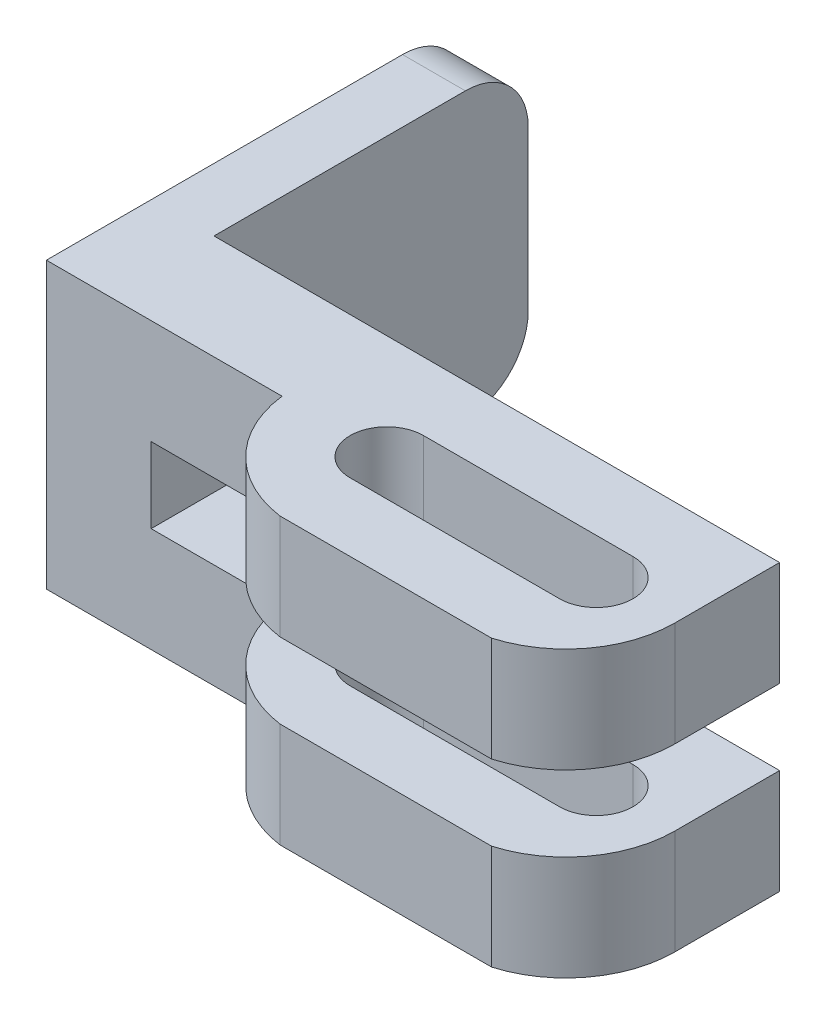
SolidWorks part; units mm, degrees
ref_plane "Alzado" through (0, 0, 0) normal (0, 0, 1) x (1, 0, 0)
ref_plane "Planta" through (0, 0, 0) normal (0, 1, 0) x (1, 0, 0)
ref_plane "Vista lateral" through (0, 0, 0) normal (1, 0, 0) x (0, 0, -1)
sketch "Croquis1" plane through (0, 0, 0) normal (0, 0, 1) x (1, 0, 0)
  line L0 (0, 0) -> (-90, 0) construction
  line L1 (-90, -6.8) -> (-90, -1.8)
  line L2 (-90, -1.8) -> (-65, -1.8)
  line L3 (-65, -1.8) -> (-65, 1.8)
  line L4 (-90, -6.8) -> (90, -6.8)
  line L5 (0, 0) -> (0, -28.0002) construction
  line L6 (-90, 6.8) -> (-90, 1.8)
  line L7 (-90, 1.8) -> (-65, 1.8)
  line L8 (-90, 6.8) -> (90, 6.8)
  line L9 (90, 6.8) -> (90, 1.8)
  line L10 (90, 1.8) -> (65, 1.8)
  line L11 (65, -1.8) -> (65, 1.8)
  line L12 (90, -6.8) -> (90, -1.8)
  line L13 (90, -1.8) -> (65, -1.8)
  point P10 (-65, 0)
  point P14 (0, 6.8)
  point P19 (0, -6.8)
  dimension "D1" = 90
  dimension "D2" = 5
  dimension "D3" = 1.8
  dimension "D4" = 25
extrude "Saliente-Extruir1" add sketch "Croquis1" along normal blind 10
sketch "Croquis2" plane through (0, 6.8, 0) normal (0, 1, 0) x (1, 0, 0)
  line L0 (0, -10) -> (0, 0) construction
  line L1 (90, -10) -> (-90, -10) construction
  line L2 (-91.25, -5) -> (90, -5) construction
  line L3 (-90, -10) -> (-90, 0) construction
  line L4 (90, -10) -> (90, 0) construction
  line L5 (-86.25, -3.25) -> (-76.25, -3.25)
  line L6 (-81.25, -3.25) -> (-81.25, -6.3963) construction
  line L7 (-86.25, -6.75) -> (-76.25, -6.75)
  line L8 (-86.25, -10) -> (-86.25, 0) construction
  line L9 (90, 0) -> (-90, 0) construction
  line L10 (-86.25, 0) -> (-90, 0)
  line L11 (-90, 0) -> (-90, -10)
  line L12 (-90, -10) -> (-86.25, -10)
  line L13 (86.25, -10) -> (86.25, 0) construction
  line L14 (81.25, -3.25) -> (81.25, -6.3963) construction
  line L15 (90, -10) -> (86.25, -10)
  line L16 (90, 0) -> (90, -10)
  line L17 (86.25, 0) -> (90, 0)
  line L18 (86.25, -6.75) -> (76.25, -6.75)
  line L19 (86.25, -3.25) -> (76.25, -3.25)
  line L20 (-71.25, -5) -> (71.25, -5)
  line L21 (-76.15, -10) -> (76.15, -10)
  arc A0 (-86.25, -3.25) -> (-86.25, -6.75) centre (-86.25, -5) ccw
  arc A1 (-76.25, -3.25) -> (-76.25, -6.75) centre (-76.25, -5) cw
  arc A2 (-86.25, 0) -> (-86.25, -10) centre (-84.7917, -5) ccw
  arc A3 (86.25, 0) -> (86.25, -10) centre (84.7917, -5) cw
  arc A4 (76.25, -3.25) -> (76.25, -6.75) centre (76.25, -5) ccw
  arc A5 (86.25, -3.25) -> (86.25, -6.75) centre (86.25, -5) cw
  arc A6 (-76.15, -10) -> (-71.25, -5) centre (-76.9399, -4.3249) ccw
  arc A7 (76.15, -10) -> (71.25, -5) centre (76.9399, -4.3249) cw
  point P13 (-88, -5)
  point P20 (-81.25, -6.75)
  point P43 (81.25, -6.75)
  point P52 (0, -5)
  line M6 (90, 0) -> (-90, 0)
  line M7 (-90, 0) -> (-90, -10)
  line M8 (-90, -10) -> (90, -10)
  line M9 (90, -10) -> (90, 0)
  dimension "D1" = 3.5
  dimension "D2" = 2
  dimension "D3" = 10
  dimension "D4" = 5
  dimension "D5" = 5
  dimension "D6" = 3.75
extrude "Cortar-Extruir1" cut sketch "Croquis2" against normal through all contours A2 M6 M7 M8 | A1 L5 A0 L7 | L21 A7 L20 A6 | A3 M6 M8 M9 | A5 L19 A4 L18
sketch "Croquis3" plane through (0, 0, 0) normal (0, 0, -1) x (-1, 0, 0)
  line L0 (0, 0) -> (0, 22.1197) construction
  line L1 (-90, 6.8) -> (86.25, 6.8) construction
  line L2 (-63, 6.8) -> (-60, 6.8)
  line L3 (-63, 6.8) -> (-63, -6.8)
  line L4 (-63, -6.8) -> (-60, -6.8)
  line L5 (-60, 6.8) -> (-60, -6.8)
  line L6 (86.25, -6.8) -> (-90, -6.8) construction
  line L7 (-65, -1.8) -> (-65, 1.8) construction
  line L8 (63, 6.8) -> (63, -6.8)
  line L9 (63, -6.8) -> (60, -6.8)
  line L10 (60, 6.8) -> (60, -6.8)
  point P17 (60, 0)
  line M1 (86.25, 6.8) -> (-90, 6.8)
  line M7 (-90, -6.8) -> (86.25, -6.8)
  dimension "D1" = 3
  dimension "D2" = 2
  dimension "D3" = 120
extrude "Saliente-Extruir2" add sketch "Croquis3" along normal blind 15 contours L5 L3 M1 M7 | L10 L8 M1 M7
chamfer "Chaflán1" distance 10 angle 15 1 edges at (0, -6.8, 0)
fillet "Redondeo1" radius 3 4 edges at (-61.5, 6.8, -15) (-61.5, -6.8, -15) (61.5, 6.8, -15) (61.5, -6.8, -15)
sketch "Croquis4" plane through (0, -6.8, 0) normal (0, -1, 0) x (-1, 0, 0)
  line L0 (-60, -24.3358) -> (-60, 24.7857)
  line L1 (-60, 12) -> (-60, -2.6795) construction
  line L2 (-60, -24.3358) -> (107.3716, -24.3358)
  line L3 (107.3716, -24.3358) -> (107.3716, 24.7857)
  line L4 (107.3716, 24.7857) -> (-60, 24.7857)
  point P4 (-60, 4.6603)
  point P5 (107.3716, 24.7857)
extrude "Cortar-Extruir2" cut sketch "Croquis4" against normal through all
